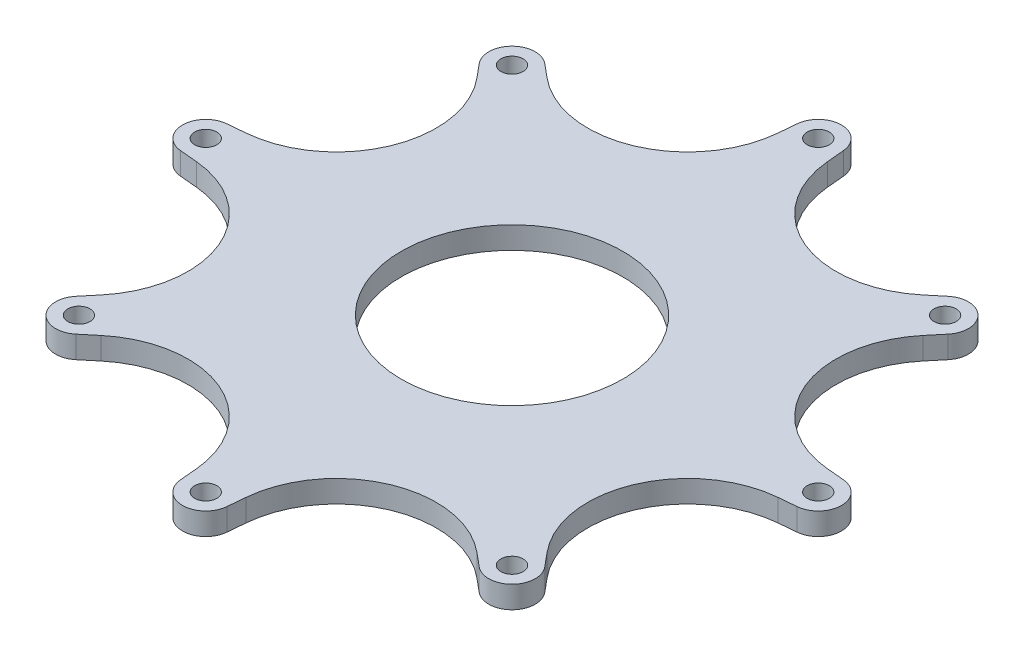
SolidWorks part; units mm, degrees
material "Thornel Mat VMA"
ref_plane "Front Plane" through (0, 0, 0) normal (0, 0, 1) x (1, 0, 0)
ref_plane "Top Plane" through (0, 0, 0) normal (0, 1, 0) x (1, 0, 0)
ref_plane "Right Plane" through (0, 0, 0) normal (1, 0, 0) x (0, 0, -1)
sketch "Sketch1" plane through (0, 0, 0) normal (0, 1, 0) x (1, 0, 0)
  line L0 (0, 0) -> (73.1675, 0) construction
  line L1 (0, 0) -> (67.598, 28) construction
  line L2 (0, 0) -> (67.598, -28) construction
  line L3 (67.598, 28) -> (67.598, -28) construction
  line L4 (69.5723, 5.2285) -> (65.5653, 5.592)
  line L5 (69.5723, -5.2285) -> (65.5653, -5.592)
  line L6 (52.8921, -45.4979) -> (50.3158, -42.4076)
  line L7 (45.4979, -52.8921) -> (42.4076, -50.3158)
  line L8 (5.2285, -69.5723) -> (5.592, -65.5653)
  line L9 (-5.2285, -69.5723) -> (-5.592, -65.5653)
  line L10 (-45.4979, -52.8921) -> (-42.4076, -50.3158)
  line L11 (-52.8921, -45.4979) -> (-50.3158, -42.4076)
  line L12 (-69.5723, -5.2285) -> (-65.5653, -5.592)
  line L13 (-69.5723, 5.2285) -> (-65.5653, 5.592)
  line L14 (-52.8921, 45.4979) -> (-50.3158, 42.4076)
  line L15 (-45.4979, 52.8921) -> (-42.4076, 50.3158)
  line L16 (-5.2285, 69.5723) -> (-5.592, 65.5653)
  line L17 (5.2285, 69.5723) -> (5.592, 65.5653)
  line L18 (45.4979, 52.8921) -> (42.4076, 50.3158)
  line L19 (52.8921, 45.4979) -> (50.3158, 42.4076)
  circle A0 centre (0, 0) radius 73.1675 construction
  circle A1 centre (67.598, 28) radius 22.5
  circle A3 centre (69.098, 0) radius 5.25
  circle A4 centre (67.598, -28) radius 22.5
  circle A5 centre (48.8597, -48.8597) radius 5.25
  circle A6 centre (28, -67.598) radius 22.5
  circle A7 centre (0, -69.098) radius 5.25
  circle A8 centre (-28, -67.598) radius 22.5
  circle A9 centre (-48.8597, -48.8597) radius 5.25
  circle A10 centre (-67.598, -28) radius 22.5
  circle A11 centre (-69.098, 0) radius 5.25
  circle A12 centre (-67.598, 28) radius 22.5
  circle A13 centre (-48.8597, 48.8597) radius 5.25
  circle A14 centre (-28, 67.598) radius 22.5
  circle A15 centre (0, 69.098) radius 5.25
  circle A16 centre (28, 67.598) radius 22.5
  circle A17 centre (48.8597, 48.8597) radius 5.25
  point P71 (0, 0)
  dimension "D1" = 45
  dimension "D5" = 10.5
  dimension "D2" = 22.5
  dimension "D3" = 22.5
  dimension "D4" = 56
  dimension "D6" = 1.5
  dimension "D7" = 8
extrude "Boss-Extrude1" add sketch "Sketch1" along normal blind 5 contours A17 L18 A16 L17 A15 L16 A14 L15 A13 L14 A12 L13 A11 L12 A10 L11 A9 L10 A8 L9 A7 L8 A6 L7 A5 L6 A4 L5 A3 L4 A1 L19 | A7 | A5 | A3 | A17 | A9 | A11 | A13 | A15
sketch "Sketch2" plane through (0, 5, 0) normal (0, 1, 0) x (1, 0, 0)
  circle A0 centre (0, 0) radius 69.098 construction
  circle A1 centre (69.098, 0) radius 2.5
  circle A2 centre (48.8597, -48.8597) radius 2.5
  circle A3 centre (0, -69.098) radius 2.5
  circle A4 centre (-48.8597, -48.8597) radius 2.5
  circle A5 centre (-69.098, 0) radius 2.5
  circle A6 centre (-48.8597, 48.8597) radius 2.5
  circle A7 centre (0, 69.098) radius 2.5
  circle A8 centre (48.8597, 48.8597) radius 2.5
  point P22 (0, 0)
  dimension "D1" = 5
  dimension "D2" = 8
extrude "Cut-Extrude1" cut sketch "Sketch2" against normal blind 10
sketch "Sketch3" plane through (0, 5, 0) normal (0, 1, 0) x (1, 0, 0)
  circle A0 centre (0, 0) radius 25
  dimension "D1" = 50
extrude "Cut-Extrude2" cut sketch "Sketch3" against normal blind 10
